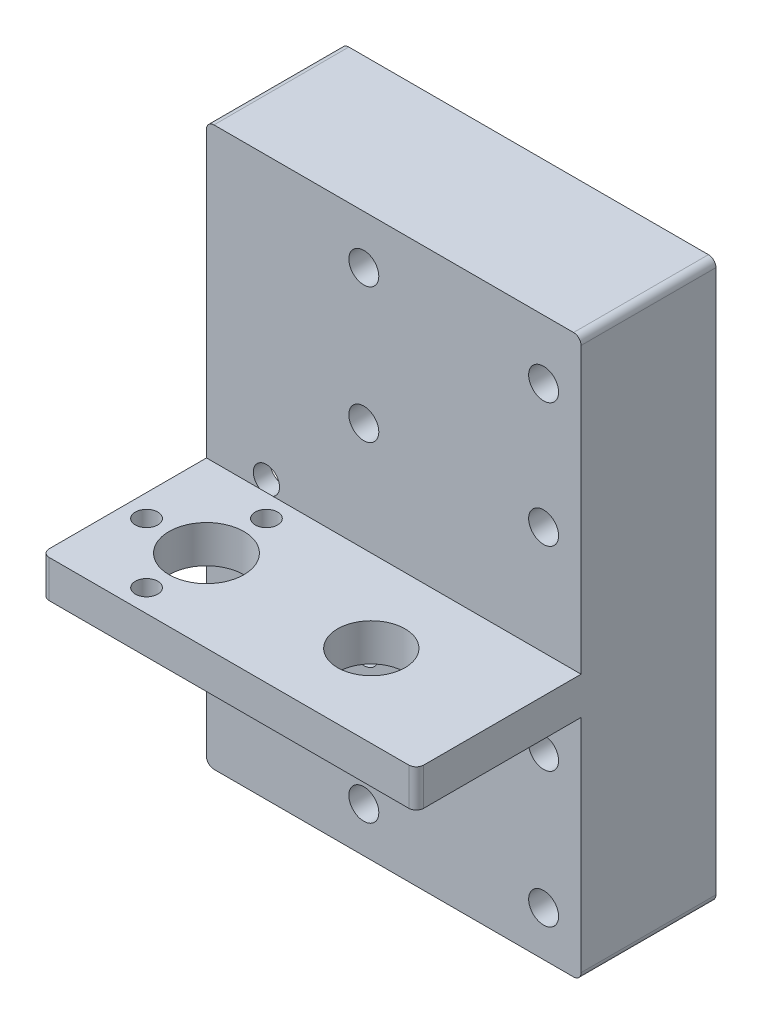
SolidWorks part; units mm, degrees
ref_plane "Front Plane" through (0, 0, 0) normal (0, 0, 1) x (1, 0, 0)
ref_plane "Top Plane" through (0, 0, 0) normal (0, 1, 0) x (1, 0, 0)
ref_plane "Right Plane" through (0, 0, 0) normal (1, 0, 0) x (0, 0, -1)
sketch "Sketch1" plane through (0, 0, 0) normal (0, 0, 1) x (1, 0, 0)
  line L0 (-9, 31.6291) -> (-9, -54.5727) construction
  line L1 (-25, -37) -> (25, -37)
  line L2 (-25, -37) -> (-25, 37)
  line L3 (-25, 37) -> (25, 37)
  line L4 (25, -37) -> (25, 37)
  line L5 (-25, -37) -> (25, 37) construction
  line L6 (-25, 37) -> (25, -37) construction
  line L7 (-31.7103, 0) -> (29.4717, 0) construction
  line L8 (8, 28.8913) -> (8, -56.8948) construction
  line L9 (-38.1073, -13) -> (73.759, -13) construction
  line L10 (-38.1073, -31) -> (69.9864, -31) construction
  line L11 (20, 28.8913) -> (20, -62.4061) construction
  line L12 (-4, 31.6291) -> (-4, -63.5871) construction
  line L13 (-32.9198, 31) -> (54.2759, 31) construction
  line L14 (-31.7103, 13) -> (56.377, 13) construction
  circle A0 centre (-4, 31) radius 2
  circle A1 centre (20, 29.6) radius 2
  circle A2 centre (20, 13) radius 2
  circle A3 centre (-4, 13) radius 2
  circle A4 centre (-4, -13) radius 2
  circle A5 centre (20, -13) radius 2
  circle A6 centre (20, -31) radius 2
  circle A7 centre (-4, -31) radius 2
  point P0 (0, 0)
  dimension "D11" = 4
  dimension "D1" = 74
  dimension "D2" = 50
  dimension "D3" = 34
  dimension "D4" = 17
  dimension "D5" = 12
  dimension "D6" = 12
  dimension "D7" = 18
  dimension "D8" = 6
  dimension "D9" = 18
  dimension "D10" = 6
extrude "Boss-Extrude1" add sketch "Sketch1" along normal blind 18
sketch "Sketch5" plane through (0, 37, 0) normal (0, 1, 0) x (1, 0, 0)
  line L0 (-25, -18) -> (-25, 0) construction
  line L1 (25, -18) -> (25, 0) construction
  line L2 (25, -18) -> (-25, -18) construction
  line L3 (25, 0) -> (-25, 0) construction
  line L4 (-25, -18) -> (-25, 0)
  line L5 (25, -18) -> (25, 0)
  line L6 (25, -18) -> (-25, -18)
  line L7 (25, 0) -> (-25, 0)
extrude "Boss-Extrude3" add sketch "Sketch5" along normal blind 5.5
sketch "Sketch7" plane through (0, 0, 18) normal (0, 0, 1) x (1, 0, 0)
  line L0 (25, -37) -> (25, 42.5) construction
  line L1 (-25, 42.5) -> (25, 42.5)
  line L2 (-25, 42.5) -> (-25, 37.5)
  line L3 (-25, 37.5) -> (25, 37.5)
  line L4 (25, 42.5) -> (25, 37.5)
  dimension "D1" = 5
extrude "Boss-Extrude5" add sketch "Sketch7" along normal blind 22
sketch "Sketch8" plane through (0, 42.5, 0) normal (0, 1, 0) x (1, 0, 0)
  line L0 (8, 2.9556) -> (8, -38.3574) construction
  line L1 (25, -40) -> (25, 0) construction
  line L2 (-14, 5.5675) -> (-14, -40.4264) construction
  line L3 (-32.4874, -29) -> (32.9367, -29) construction
  circle A0 centre (8, -29) radius 4.5
  circle A1 centre (-14, -29) radius 5
  dimension "D4" = 9
  dimension "D5" = 10
  dimension "D1" = 17
  dimension "D2" = 22
  dimension "D3" = 11
extrude "Cut-Extrude1" cut sketch "Sketch8" against normal up to next
sketch "Sketch10" plane through (-25, 0, 0) normal (-1, 0, 0) x (0, 0, 1)
  line L0 (-17.1535, -22) -> (39.1951, -22) construction
  line L1 (18, -37) -> (0, -37) construction
  line L2 (-26.6224, 22) -> (44.96, 22) construction
  line L4 (40, 37.5) -> (18, 37.5) construction
  line L5 (9, 40.6238) -> (9, -39.2385) construction
  line L6 (18, 37.5) -> (18, -37) construction
  line L7 (-15.363, 0) -> (36.6289, 0) construction
  line L9 (2.25, -10) -> (15.75, -10)
  line L10 (2.25, -10) -> (2.25, 10)
  line L11 (2.25, 10) -> (15.75, 10)
  line L12 (15.75, -10) -> (15.75, 10)
  line L13 (2.25, -10) -> (15.75, 10) construction
  line L14 (2.25, 10) -> (15.75, -10) construction
  circle A0 centre (9, 22) radius 3.95
  circle A1 centre (9, -22) radius 3.95
  point P17 (9, 0)
  dimension "D4" = 7.9
  dimension "D1" = 15
  dimension "D2" = 15.5
  dimension "D3" = 9
  dimension "D5" = 13.5
  dimension "D6" = 20
extrude "Cut-Extrude2" cut sketch "Sketch10" against normal blind 20
sketch "Sketch11" plane through (0, 0, 18) normal (0, 0, 1) x (1, 0, 0)
  line L0 (-43.243, 0) -> (45.6454, 0) construction
  line L2 (-17, 46.6546) -> (-17, -40.0349) construction
  line L3 (-25, 37.5) -> (-25, -37) construction
  circle A0 centre (-17, 0) radius 1.75
  dimension "D3" = 3.5
  dimension "D2" = 8
extrude "Cut-Extrude3" cut sketch "Sketch11" against normal up to surface (18 mm away) up to face at (22, -31, 0)
fillet "Fillet2" radius 1 4 edges at (25, -37, 9) (-25, -37, 9) (-25, 42.5, 20) (25, 42.5, 20)
sketch "Sketch12" plane through (0, 42.5, 0) normal (0, 1, 0) x (1, 0, 0)
  line L0 (24, -40) -> (25, -40) construction
  line L1 (-25, -40) -> (-24, -40) construction
  line L2 (25, 0) -> (25, -40) construction
  line L3 (24, -40) -> (-24, -40) construction
  line L4 (-25, -40) -> (-25, 0) construction
  line L5 (24, -40) -> (25, -40)
  line L6 (-25, -40) -> (-24, -40)
  line L7 (25, -18) -> (25, -40)
  line L8 (24, -40) -> (-24, -40)
  line L9 (-25, -40) -> (-25, -18)
  line L10 (-25, -18) -> (25, -18)
  circle A0 centre (-14, -29) radius 5 construction
  circle A1 centre (8, -29) radius 4.5 construction
  circle A2 centre (-14, -29) radius 5
  circle A3 centre (8, -29) radius 4.5
  dimension "D1" = 11
extrude "Boss-Extrude6" add sketch "Sketch12" along normal blind 5 from offset 49 offset against normal yes
sketch "Sketch13" plane through (0, 0, 40) normal (0, 0, 1) x (1, 0, 0)
  line L0 (25, 37.5) -> (25, 41.5) construction
  line L1 (24, 42.5) -> (-24, 42.5) construction
  line L2 (-25, 41.5) -> (-25, 37.5) construction
  line L3 (-25, 37.5) -> (25, 37.5) construction
  line L4 (25, 37.5) -> (25, 41.5)
  line L5 (24, 42.5) -> (-24, 42.5)
  line L6 (-25, 41.5) -> (-25, 37.5)
  line L7 (-25, 37.5) -> (25, 37.5)
  arc A0 (25, 41.5) -> (24, 42.5) centre (24, 41.5) ccw construction
  arc A1 (-24, 42.5) -> (-25, 41.5) centre (-24, 41.5) ccw construction
  arc A2 (25, 41.5) -> (24, 42.5) centre (24, 41.5) ccw
  arc A3 (-24, 42.5) -> (-25, 41.5) centre (-24, 41.5) ccw
extrude "Cut-Extrude4" cut sketch "Sketch13" against normal up to next
fillet "Fillet3" radius 1 4 edges at (25, -4, 40) (-25, -4, 40) (25, 37.5, 9) (-25, 37.5, 9)
sketch "Sketch14" plane through (0, -1.5, 0) normal (0, 1, 0) x (1, 0, 0)
  line L0 (-14, -15.4544) -> (-14, -42.978) construction
  line L1 (-28.5244, -29) -> (-1.5013, -29) construction
  circle A0 centre (-14, -21) radius 1.5
  circle A1 centre (-22, -29) radius 1.5
  circle A2 centre (-14, -37) radius 1.5
  dimension "D1" = 3
  dimension "D2" = 8
  dimension "D4" = 8
  dimension "D3" = 8
extrude "Cut-Extrude5" cut sketch "Sketch14" against normal up to next
